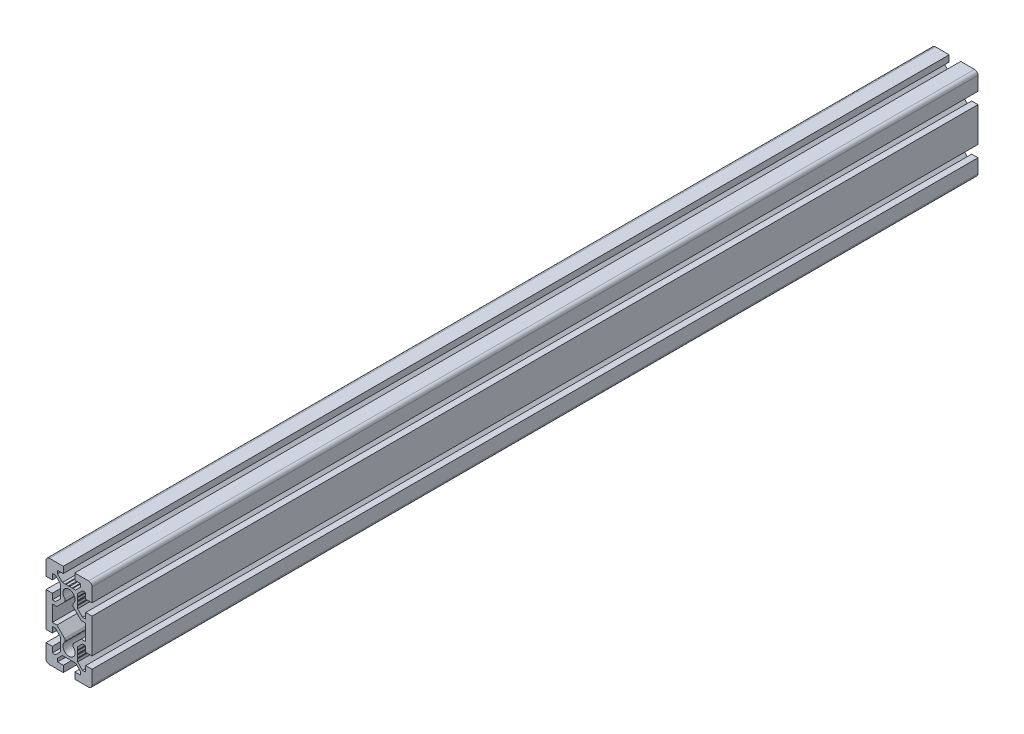
SolidWorks part; units mm, degrees
material "6061-T6 (SS)"
ref_plane "Front Plane" through (0, 0, 0) normal (0, 0, 1) x (1, 0, 0)
ref_plane "Top Plane" through (0, 0, 0) normal (0, 1, 0) x (1, 0, 0)
ref_plane "Right Plane" through (0, 0, 0) normal (1, 0, 0) x (0, 0, -1)
sketch "Sketch1" plane through (0, 0, 0) normal (0, 0, 1) x (1, 0, 0)
  line L0 (-10.5251, -7) -> (-14.5, -7)
  line L1 (-14.5, -7) -> (-14.5, 7)
  line L2 (-14.5, 7) -> (-10.5251, 7)
  line L3 (-10.5251, 7) -> (-3.886, 13.6391)
  line L4 (10.5251, 7) -> (14.5, 7)
  line L5 (14.5, 7) -> (14.5, -7)
  line L6 (14.5, -7) -> (10.5251, -7)
  line L7 (-14.5, 10) -> (-14.5, 15)
  line L8 (-14.5, 15) -> (-20, 15)
  line L9 (-20, 15) -> (-20, -15)
  line L10 (-20, -15) -> (-14.5, -15)
  line L11 (-14.5, -15) -> (-14.5, -10)
  line L12 (-14.5, -10) -> (-11.7678, -10)
  line L13 (-7.5, -14.2678) -> (-7.5, -16.6536)
  line L14 (-7.5, -16.6536) -> (-7.3, -17)
  line L15 (-7.3, -17) -> (-7.5, -17.3464)
  line L16 (-7.5, -17.3464) -> (-7.5, -19.4804)
  line L17 (-7.5, -19.4804) -> (-7.2, -20)
  line L18 (-7.2, -20) -> (-7.5, -20.5196)
  line L19 (-7.5, -20.5196) -> (-7.5, -22.6536)
  line L20 (-7.5, -22.6536) -> (-7.3, -23)
  line L21 (-7.3, -23) -> (-7.5, -23.3464)
  line L22 (-7.5, -23.3464) -> (-7.5, -25.7322)
  line L23 (-11.7678, -30) -> (-14.5, -30)
  line L24 (-14.5, -30) -> (-14.5, -25)
  line L25 (-14.5, -25) -> (-20, -25)
  line L26 (-20, -25) -> (-20, -37)
  line L27 (-17, -40) -> (-5, -40)
  line L28 (-5, -40) -> (-5, -34.5)
  line L29 (-5, -34.5) -> (-10, -34.5)
  line L30 (-10, -34.5) -> (-10, -31.7678)
  line L31 (-5.7322, -27.5) -> (-3.3464, -27.5)
  line L32 (-3.3464, -27.5) -> (-3, -27.3)
  line L33 (-3, -27.3) -> (-2.6536, -27.5)
  line L34 (-2.6536, -27.5) -> (-0.5196, -27.5)
  line L35 (-0.5196, -27.5) -> (0, -27.2)
  line L36 (0, -27.2) -> (0.5196, -27.5)
  line L37 (0.5196, -27.5) -> (2.6536, -27.5)
  line L38 (2.6536, -27.5) -> (3, -27.3)
  line L39 (3, -27.3) -> (3.3464, -27.5)
  line L40 (3.3464, -27.5) -> (5.7322, -27.5)
  line L41 (10, -31.7678) -> (10, -34.5)
  line L42 (10, -34.5) -> (5, -34.5)
  line L43 (5, -34.5) -> (5, -40)
  line L44 (5, -40) -> (17, -40)
  line L45 (20, -37) -> (20, -25)
  line L46 (20, -25) -> (14.5, -25)
  line L47 (14.5, -25) -> (14.5, -30)
  line L48 (14.5, -30) -> (11.7678, -30)
  line L49 (7.5, -25.7322) -> (7.5, -23.3464)
  line L50 (7.5, -23.3464) -> (7.3, -23)
  line L51 (7.3, -23) -> (7.5, -22.6536)
  line L52 (7.5, -22.6536) -> (7.5, -20.5196)
  line L53 (7.5, -20.5196) -> (7.2, -20)
  line L54 (7.2, -20) -> (7.5, -19.4804)
  line L55 (7.5, -19.4804) -> (7.5, -17.3464)
  line L56 (7.5, -17.3464) -> (7.3, -17)
  line L57 (7.3, -17) -> (7.5, -16.6536)
  line L58 (7.5, -16.6536) -> (7.5, -14.2678)
  line L59 (11.7678, -10) -> (14.5, -10)
  line L60 (14.5, -10) -> (14.5, -15)
  line L61 (14.5, -15) -> (20, -15)
  line L62 (20, -15) -> (20, 15)
  line L63 (20, 15) -> (14.5, 15)
  line L64 (14.5, 15) -> (14.5, 10)
  line L65 (14.5, 10) -> (11.7678, 10)
  line L66 (7.5, 14.2678) -> (7.5, 16.6536)
  line L67 (7.5, 16.6536) -> (7.3, 17)
  line L68 (7.3, 17) -> (7.5, 17.3464)
  line L69 (7.5, 17.3464) -> (7.5, 19.4804)
  line L70 (7.5, 19.4804) -> (7.2, 20)
  line L71 (7.2, 20) -> (7.5, 20.5196)
  line L72 (7.5, 20.5196) -> (7.5, 22.6536)
  line L73 (7.5, 22.6536) -> (7.3, 23)
  line L74 (7.3, 23) -> (7.5, 23.3464)
  line L75 (7.5, 23.3464) -> (7.5, 25.7322)
  line L76 (11.7678, 30) -> (14.5, 30)
  line L77 (14.5, 30) -> (14.5, 25)
  line L78 (14.5, 25) -> (20, 25)
  line L79 (20, 25) -> (20, 37)
  line L80 (17, 40) -> (5, 40)
  line L81 (5, 40) -> (5, 34.5)
  line L82 (5, 34.5) -> (10, 34.5)
  line L83 (10, 34.5) -> (10, 31.7678)
  line L84 (5.7322, 27.5) -> (3.3464, 27.5)
  line L85 (3.3464, 27.5) -> (3, 27.3)
  line L86 (3, 27.3) -> (2.6536, 27.5)
  line L87 (2.6536, 27.5) -> (0.5196, 27.5)
  line L88 (0.5196, 27.5) -> (0, 27.2)
  line L89 (0, 27.2) -> (-0.5196, 27.5)
  line L90 (-0.5196, 27.5) -> (-2.6536, 27.5)
  line L91 (-2.6536, 27.5) -> (-3, 27.3)
  line L92 (-3, 27.3) -> (-3.3464, 27.5)
  line L93 (-3.3464, 27.5) -> (-5.7322, 27.5)
  line L94 (-10, 31.7678) -> (-10, 34.5)
  line L95 (-10, 34.5) -> (-5, 34.5)
  line L96 (-5, 34.5) -> (-5, 40)
  line L97 (-5, 40) -> (-17, 40)
  line L98 (-20, 37) -> (-20, 25)
  line L99 (-20, 25) -> (-14.5, 25)
  line L100 (-14.5, 25) -> (-14.5, 30)
  line L101 (-14.5, 30) -> (-11.7678, 30)
  line L102 (-7.5, 25.7322) -> (-7.5, 23.3464)
  line L103 (-7.5, 23.3464) -> (-7.3, 23)
  line L104 (-7.3, 23) -> (-7.5, 22.6536)
  line L105 (-7.5, 22.6536) -> (-7.5, 20.5196)
  line L106 (-7.5, 20.5196) -> (-7.2, 20)
  line L107 (-7.2, 20) -> (-7.5, 19.4804)
  line L108 (-7.5, 19.4804) -> (-7.5, 17.3464)
  line L109 (-7.5, 17.3464) -> (-7.3, 17)
  line L110 (-7.3, 17) -> (-7.5, 16.6536)
  line L111 (-7.5, 16.6536) -> (-7.5, 14.2678)
  line L112 (-11.7678, 10) -> (-14.5, 10)
  arc A0 (-3.886, 13.6391) -> (-3.8381, 16.4179) centre (-5.3003, 15.0533) ccw
  arc A1 (-3.8381, 16.4179) -> (3.8381, 16.4179) centre (0, 20) cw
  arc A2 (3.8381, 16.4179) -> (3.886, 13.6391) centre (5.3003, 15.0533) ccw
  arc A3 (3.886, -13.6391) -> (3.8381, -16.4179) centre (5.3003, -15.0533) ccw
  arc A4 (3.8381, -16.4179) -> (-3.8381, -16.4179) centre (0, -20) cw
  arc A5 (-3.8381, -16.4179) -> (-3.886, -13.6391) centre (-5.3003, -15.0533) ccw
  arc A6 (-20, -37) -> (-17, -40) centre (-17, -37) ccw
  arc A7 (17, -40) -> (20, -37) centre (17, -37) ccw
  arc A8 (20, 37) -> (17, 40) centre (17, 37) ccw
  arc A9 (-17, 40) -> (-20, 37) centre (-17, 37) ccw
  spline S0 degree 3 poles (-3.886, -13.6391) (-6.0991, -11.4261) (-8.3121, -9.213) (-10.5251, -7) knots 0 0 0 0 1 1 1 1
  spline S1 degree 3 poles (3.886, 13.6391) (6.0991, 11.4261) (8.3121, 9.213) (10.5251, 7) knots 0 0 0 0 1 1 1 1
  spline S2 degree 3 poles (10.5251, -7) (8.3121, -9.213) (6.0991, -11.4261) (3.886, -13.6391) knots 0 0 0 0 1 1 1 1
  spline S3 degree 3 poles (-11.7678, -10) (-10.3452, -11.4226) (-8.9226, -12.8452) (-7.5, -14.2678) knots 0 0 0 0 1 1 1 1
  spline S4 degree 3 poles (-7.5, -25.7322) (-8.9226, -27.1548) (-10.3452, -28.5774) (-11.7678, -30) knots 0 0 0 0 1 1 1 1
  spline S5 degree 3 poles (-10, -31.7678) (-8.5774, -30.3452) (-7.1548, -28.9226) (-5.7322, -27.5) knots 0 0 0 0 1 1 1 1
  spline S6 degree 3 poles (5.7322, -27.5) (7.1548, -28.9226) (8.5774, -30.3452) (10, -31.7678) knots 0 0 0 0 1 1 1 1
  spline S7 degree 3 poles (11.7678, -30) (10.3452, -28.5774) (8.9226, -27.1548) (7.5, -25.7322) knots 0 0 0 0 1 1 1 1
  spline S8 degree 3 poles (7.5, -14.2678) (8.9226, -12.8452) (10.3452, -11.4226) (11.7678, -10) knots 0 0 0 0 1 1 1 1
  spline S9 degree 3 poles (11.7678, 10) (10.3452, 11.4226) (8.9226, 12.8452) (7.5, 14.2678) knots 0 0 0 0 1 1 1 1
  spline S10 degree 3 poles (7.5, 25.7322) (8.9226, 27.1548) (10.3452, 28.5774) (11.7678, 30) knots 0 0 0 0 1 1 1 1
  spline S11 degree 3 poles (10, 31.7678) (8.5774, 30.3452) (7.1548, 28.9226) (5.7322, 27.5) knots 0 0 0 0 1 1 1 1
  spline S12 degree 3 poles (-5.7322, 27.5) (-7.1548, 28.9226) (-8.5774, 30.3452) (-10, 31.7678) knots 0 0 0 0 1 1 1 1
  spline S13 degree 3 poles (-11.7678, 30) (-10.3452, 28.5774) (-8.9226, 27.1548) (-7.5, 25.7322) knots 0 0 0 0 1 1 1 1
  spline S14 degree 3 poles (-7.5, 14.2678) (-8.9226, 12.8452) (-10.3452, 11.4226) (-11.7678, 10) knots 0 0 0 0 1 1 1 1
extrude "Boss-Extrude1" add sketch "Sketch1" against normal blind 770
